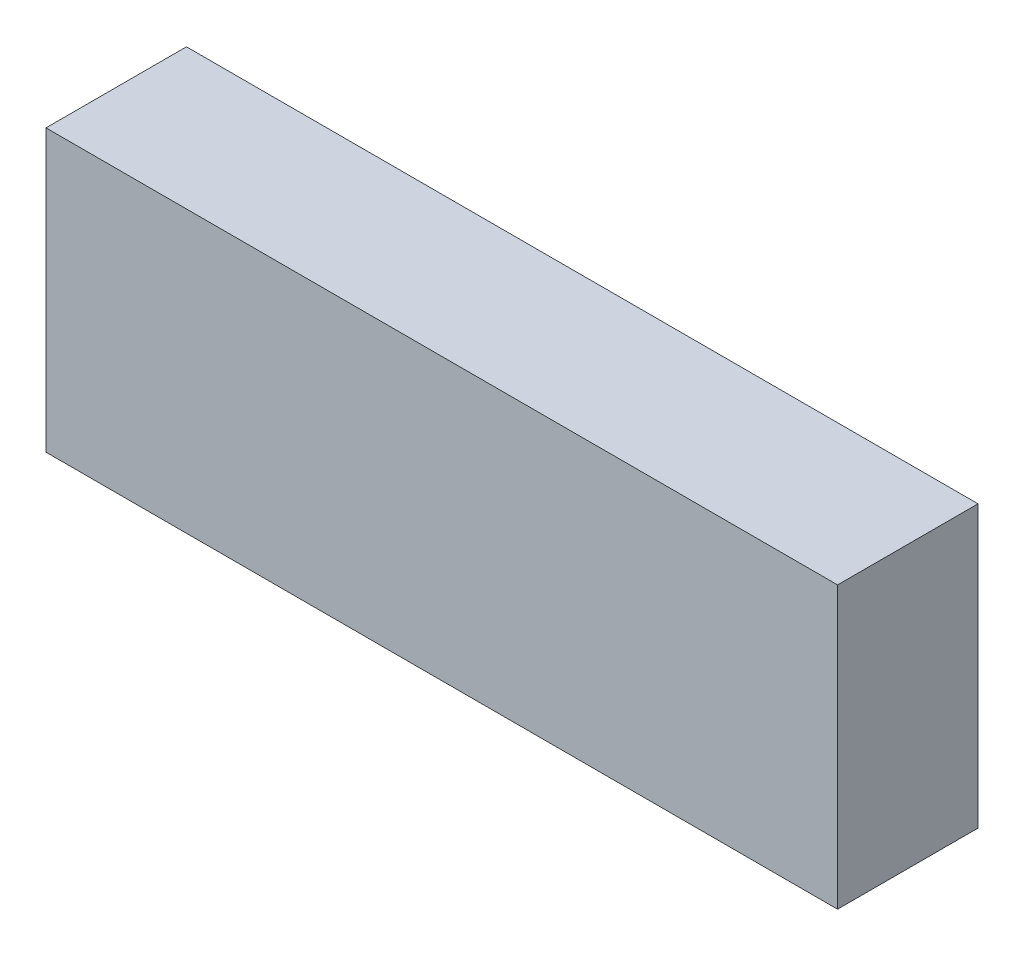
SolidWorks part; units mm, degrees
material "Custom Plastic"
ref_plane "Front Plane" through (0, 0, 0) normal (0, 0, 1) x (1, 0, 0)
ref_plane "Top Plane" through (0, 0, 0) normal (0, 1, 0) x (1, 0, 0)
ref_plane "Right Plane" through (0, 0, 0) normal (1, 0, 0) x (0, 0, -1)
sketch "Sketch1" plane through (0, 0, 0) normal (0, 0, 1) x (1, 0, 0)
  line L3 (6.5732, -7.0427) -> (-24.4268, -7.0427)
  line L4 (6.5732, -7.0427) -> (6.5732, 3.9573)
  line L5 (6.5732, 3.9573) -> (-24.4268, 3.9573)
  line L6 (-24.4268, -7.0427) -> (-24.4268, 3.9573)
  dimension "D1" = 11
  dimension "D2" = 31
extrude "Boss-Extrude1" add sketch "Sketch1" along normal blind 5.5
